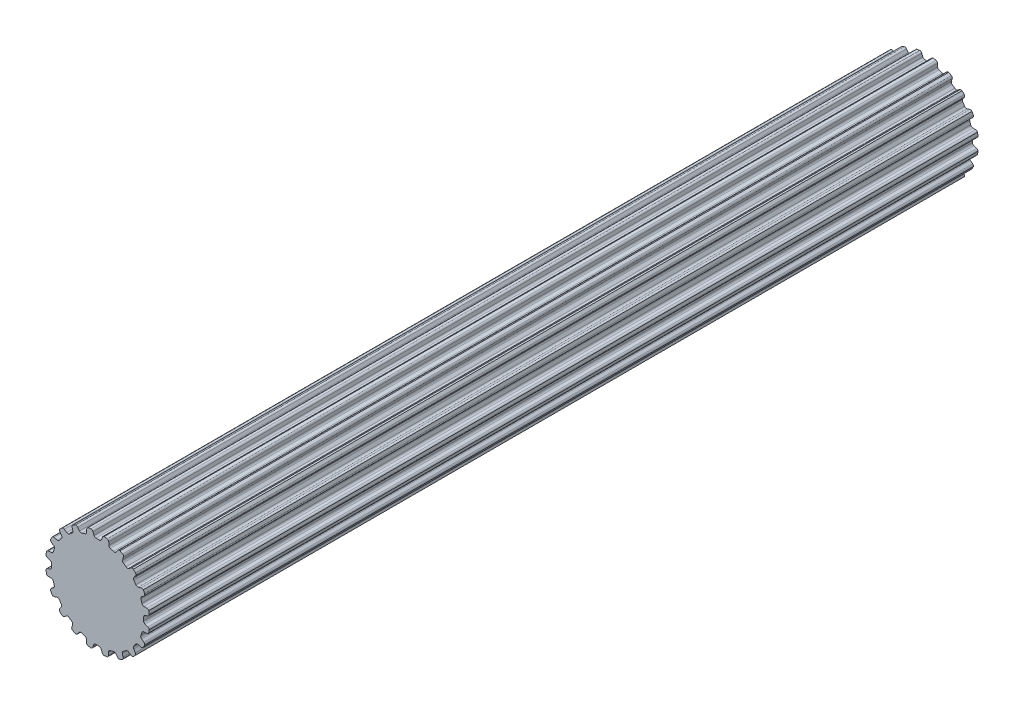
SolidWorks part; units mm, degrees
ref_plane "Front Plane" through (0, 0, 0) normal (0, 0, 1) x (1, 0, 0)
ref_plane "Top Plane" through (0, 0, 0) normal (0, 1, 0) x (1, 0, 0)
ref_plane "Right Plane" through (0, 0, 0) normal (1, 0, 0) x (0, 0, -1)
sketch "Sketch1" plane through (0, 0, 0) normal (0, 0, 1) x (1, 0, 0)
  line L0 (-0.1069, 2.9699) -> (0.1069, 2.9699)
  line L1 (0.3159, 3.2375) -> (0.2537, 3.0575)
  line L2 (-0.2964, 3.2367) -> (-0.2318, 3.0575)
  line L3 (-0.2964, 3.2367) -> (0.3159, 3.2375) construction
  line L4 (0, 3.3252) -> (0, 0) construction
  line L5 (-0.2318, 3.0575) -> (0.2537, 3.0575) construction
  line L6 (-0.4281, 3.3241) -> (0.4281, 3.3263) construction
  line L7 (0.7183, 3.1698) -> (0.7244, 2.9795)
  line L8 (0.816, 2.8576) -> (1.0195, 2.7915)
  line L9 (1.3009, 2.9815) -> (1.1862, 2.8295)
  line L10 (1.6627, 2.7927) -> (1.6097, 2.6099)
  line L11 (1.6591, 2.4655) -> (1.8322, 2.3398)
  line L12 (2.1585, 2.4335) -> (2.0025, 2.3245)
  line L13 (2.4443, 2.1423) -> (2.3374, 1.9847)
  line L14 (2.3398, 1.8322) -> (2.4655, 1.6591)
  line L15 (2.8049, 1.6474) -> (2.6228, 1.5919)
  line L16 (2.9866, 1.2821) -> (2.8363, 1.1653)
  line L17 (2.7915, 1.0195) -> (2.8576, 0.816)
  line L18 (3.1767, 0.7) -> (2.9863, 0.7035)
  line L19 (3.2367, 0.2964) -> (3.0575, 0.2318)
  line L20 (2.9699, 0.1069) -> (2.9699, -0.1069)
  line L21 (3.2375, -0.3159) -> (3.0575, -0.2537)
  line L22 (3.1698, -0.7183) -> (2.9795, -0.7244)
  line L23 (2.8576, -0.816) -> (2.7915, -1.0195)
  line L24 (2.9815, -1.3009) -> (2.8295, -1.1862)
  line L25 (2.7927, -1.6627) -> (2.6099, -1.6097)
  line L26 (2.4655, -1.6591) -> (2.3398, -1.8322)
  line L27 (2.4335, -2.1585) -> (2.3245, -2.0025)
  line L28 (2.1423, -2.4443) -> (1.9847, -2.3374)
  line L29 (1.8322, -2.3398) -> (1.6591, -2.4655)
  line L30 (1.6474, -2.8049) -> (1.5919, -2.6228)
  line L31 (1.2821, -2.9866) -> (1.1653, -2.8363)
  line L32 (1.0195, -2.7915) -> (0.816, -2.8576)
  line L33 (0.7, -3.1767) -> (0.7035, -2.9863)
  line L34 (0.2964, -3.2367) -> (0.2318, -3.0575)
  line L35 (0.1069, -2.9699) -> (-0.1069, -2.9699)
  line L36 (-0.3159, -3.2375) -> (-0.2537, -3.0575)
  line L37 (-0.7183, -3.1698) -> (-0.7244, -2.9795)
  line L38 (-0.816, -2.8576) -> (-1.0195, -2.7915)
  line L39 (-1.3009, -2.9815) -> (-1.1862, -2.8295)
  line L40 (-1.6627, -2.7927) -> (-1.6097, -2.6099)
  line L41 (-1.6591, -2.4655) -> (-1.8322, -2.3398)
  line L42 (-2.1585, -2.4335) -> (-2.0025, -2.3245)
  line L43 (-2.4443, -2.1423) -> (-2.3374, -1.9847)
  line L44 (-2.3398, -1.8322) -> (-2.4655, -1.6591)
  line L45 (-2.8049, -1.6474) -> (-2.6228, -1.5919)
  line L46 (-2.9866, -1.2821) -> (-2.8363, -1.1653)
  line L47 (-2.7915, -1.0195) -> (-2.8576, -0.816)
  line L48 (-3.1767, -0.7) -> (-2.9863, -0.7035)
  line L49 (-3.2367, -0.2964) -> (-3.0575, -0.2318)
  line L50 (-2.9699, -0.1069) -> (-2.9699, 0.1069)
  line L51 (-3.2375, 0.3159) -> (-3.0575, 0.2537)
  line L52 (-3.1698, 0.7183) -> (-2.9795, 0.7244)
  line L53 (-2.8576, 0.816) -> (-2.7915, 1.0195)
  line L54 (-2.9815, 1.3009) -> (-2.8295, 1.1862)
  line L55 (-2.7927, 1.6627) -> (-2.6099, 1.6097)
  line L56 (-2.4655, 1.6591) -> (-2.3398, 1.8322)
  line L57 (-2.4335, 2.1585) -> (-2.3245, 2.0025)
  line L58 (-2.1423, 2.4443) -> (-1.9847, 2.3374)
  line L59 (-1.8322, 2.3398) -> (-1.6591, 2.4655)
  line L60 (-1.6474, 2.8049) -> (-1.5919, 2.6228)
  line L61 (-1.2821, 2.9866) -> (-1.1653, 2.8363)
  line L62 (-1.0195, 2.7915) -> (-0.816, 2.8576)
  line L63 (-0.7, 3.1767) -> (-0.7035, 2.9863)
  line L64 (0.4281, 3.3263) -> (0.62, 3.2938)
  line L65 (1.4351, 3.0312) -> (1.6075, 2.9409)
  line L66 (2.3015, 2.4394) -> (2.4376, 2.3003)
  line L67 (2.9427, 1.6088) -> (3.0291, 1.4344)
  line L68 (3.2958, 0.6207) -> (3.3241, 0.4281)
  line L69 (3.3263, -0.4281) -> (3.2938, -0.62)
  line L70 (3.0312, -1.4351) -> (2.9409, -1.6075)
  line L71 (2.4394, -2.3015) -> (2.3003, -2.4376)
  line L72 (1.6088, -2.9427) -> (1.4344, -3.0291)
  line L73 (0.6207, -3.2958) -> (0.4281, -3.3241)
  line L74 (-0.4281, -3.3263) -> (-0.62, -3.2938)
  line L75 (-1.4351, -3.0312) -> (-1.6075, -2.9409)
  line L76 (-2.3015, -2.4394) -> (-2.4376, -2.3003)
  line L77 (-2.9427, -1.6088) -> (-3.0291, -1.4344)
  line L78 (-3.2958, -0.6207) -> (-3.3241, -0.4281)
  line L79 (-3.3263, 0.4281) -> (-3.2938, 0.62)
  line L80 (-3.0312, 1.4351) -> (-2.9409, 1.6075)
  line L81 (-2.4394, 2.3015) -> (-2.3003, 2.4376)
  line L82 (-1.6088, 2.9427) -> (-1.4344, 3.0291)
  line L83 (-0.6207, 3.2958) -> (-0.4281, 3.3241)
  arc A0 (0.2537, 3.0575) -> (0.1069, 2.9699) centre (0.1283, 3.1009) cw
  arc A1 (-0.2318, 3.0575) -> (-0.1069, 2.9699) centre (-0.1069, 3.1026) ccw
  arc A2 (0.62, 3.2938) -> (0.7183, 3.1698) centre (0.5856, 3.1656) cw
  arc A3 (0.7244, 2.9795) -> (0.816, 2.8576) centre (0.857, 2.9838) ccw
  arc A4 (-0.4281, 3.3241) -> (-0.2964, 3.2367) centre (-0.4213, 3.1916) cw
  arc A5 (0.4281, 3.3263) -> (0.3159, 3.2375) centre (0.4413, 3.1942) ccw
  arc A6 (1.1862, 2.8295) -> (1.0195, 2.7915) centre (1.0802, 2.9095) cw
  arc A7 (1.4351, 3.0312) -> (1.3009, 2.9815) centre (1.4068, 2.9015) ccw
  arc A8 (1.6075, 2.9409) -> (1.6627, 2.7927) centre (1.5352, 2.8297) cw
  arc A9 (1.6097, 2.6099) -> (1.6591, 2.4655) centre (1.7371, 2.5729) ccw
  arc A10 (2.0025, 2.3245) -> (1.8322, 2.3398) centre (1.9264, 2.4332) cw
  arc A11 (2.3015, 2.4394) -> (2.1585, 2.4335) centre (2.2346, 2.3248) ccw
  arc A12 (2.4376, 2.3003) -> (2.4443, 2.1423) centre (2.3345, 2.2168) cw
  arc A13 (2.3374, 1.9847) -> (2.3398, 1.8322) centre (2.4472, 1.9102) ccw
  arc A14 (2.6228, 1.5919) -> (2.4655, 1.6591) centre (2.5841, 1.7189) cw
  arc A15 (2.9427, 1.6088) -> (2.8049, 1.6474) centre (2.8436, 1.5205) ccw
  arc A16 (3.0291, 1.4344) -> (2.9866, 1.2821) centre (2.9052, 1.3869) cw
  arc A17 (2.8363, 1.1653) -> (2.7915, 1.0195) centre (2.9177, 1.0605) ccw
  arc A18 (2.9863, 0.7035) -> (2.8576, 0.816) centre (2.9887, 0.8362) cw
  arc A19 (3.2958, 0.6207) -> (3.1767, 0.7) centre (3.1743, 0.5673) ccw
  arc A20 (3.3241, 0.4281) -> (3.2367, 0.2964) centre (3.1916, 0.4213) cw
  arc A21 (3.0575, 0.2318) -> (2.9699, 0.1069) centre (3.1026, 0.1069) ccw
  arc A22 (3.0575, -0.2537) -> (2.9699, -0.1069) centre (3.1009, -0.1283) cw
  arc A23 (3.3263, -0.4281) -> (3.2375, -0.3159) centre (3.1942, -0.4413) ccw
  arc A24 (3.2938, -0.62) -> (3.1698, -0.7183) centre (3.1656, -0.5856) cw
  arc A25 (2.9795, -0.7244) -> (2.8576, -0.816) centre (2.9838, -0.857) ccw
  arc A26 (2.8295, -1.1862) -> (2.7915, -1.0195) centre (2.9095, -1.0802) cw
  arc A27 (3.0312, -1.4351) -> (2.9815, -1.3009) centre (2.9015, -1.4068) ccw
  arc A28 (2.9409, -1.6075) -> (2.7927, -1.6627) centre (2.8297, -1.5352) cw
  arc A29 (2.6099, -1.6097) -> (2.4655, -1.6591) centre (2.5729, -1.7371) ccw
  arc A30 (2.3245, -2.0025) -> (2.3398, -1.8322) centre (2.4332, -1.9264) cw
  arc A31 (2.4394, -2.3015) -> (2.4335, -2.1585) centre (2.3248, -2.2346) ccw
  arc A32 (2.3003, -2.4376) -> (2.1423, -2.4443) centre (2.2168, -2.3345) cw
  arc A33 (1.9847, -2.3374) -> (1.8322, -2.3398) centre (1.9102, -2.4472) ccw
  arc A34 (1.5919, -2.6228) -> (1.6591, -2.4655) centre (1.7189, -2.5841) cw
  arc A35 (1.6088, -2.9427) -> (1.6474, -2.8049) centre (1.5205, -2.8436) ccw
  arc A36 (1.4344, -3.0291) -> (1.2821, -2.9866) centre (1.3869, -2.9052) cw
  arc A37 (1.1653, -2.8363) -> (1.0195, -2.7915) centre (1.0605, -2.9177) ccw
  arc A38 (0.7035, -2.9863) -> (0.816, -2.8576) centre (0.8362, -2.9887) cw
  arc A39 (0.6207, -3.2958) -> (0.7, -3.1767) centre (0.5673, -3.1743) ccw
  arc A40 (0.4281, -3.3241) -> (0.2964, -3.2367) centre (0.4213, -3.1916) cw
  arc A41 (0.2318, -3.0575) -> (0.1069, -2.9699) centre (0.1069, -3.1026) ccw
  arc A42 (-0.2537, -3.0575) -> (-0.1069, -2.9699) centre (-0.1283, -3.1009) cw
  arc A43 (-0.4281, -3.3263) -> (-0.3159, -3.2375) centre (-0.4413, -3.1942) ccw
  arc A44 (-0.62, -3.2938) -> (-0.7183, -3.1698) centre (-0.5856, -3.1656) cw
  arc A45 (-0.7244, -2.9795) -> (-0.816, -2.8576) centre (-0.857, -2.9838) ccw
  arc A46 (-1.1862, -2.8295) -> (-1.0195, -2.7915) centre (-1.0802, -2.9095) cw
  arc A47 (-1.4351, -3.0312) -> (-1.3009, -2.9815) centre (-1.4068, -2.9015) ccw
  arc A48 (-1.6075, -2.9409) -> (-1.6627, -2.7927) centre (-1.5352, -2.8297) cw
  arc A49 (-1.6097, -2.6099) -> (-1.6591, -2.4655) centre (-1.7371, -2.5729) ccw
  arc A50 (-2.0025, -2.3245) -> (-1.8322, -2.3398) centre (-1.9264, -2.4332) cw
  arc A51 (-2.3015, -2.4394) -> (-2.1585, -2.4335) centre (-2.2346, -2.3248) ccw
  arc A52 (-2.4376, -2.3003) -> (-2.4443, -2.1423) centre (-2.3345, -2.2168) cw
  arc A53 (-2.3374, -1.9847) -> (-2.3398, -1.8322) centre (-2.4472, -1.9102) ccw
  arc A54 (-2.6228, -1.5919) -> (-2.4655, -1.6591) centre (-2.5841, -1.7189) cw
  arc A55 (-2.9427, -1.6088) -> (-2.8049, -1.6474) centre (-2.8436, -1.5205) ccw
  arc A56 (-3.0291, -1.4344) -> (-2.9866, -1.2821) centre (-2.9052, -1.3869) cw
  arc A57 (-2.8363, -1.1653) -> (-2.7915, -1.0195) centre (-2.9177, -1.0605) ccw
  arc A58 (-2.9863, -0.7035) -> (-2.8576, -0.816) centre (-2.9887, -0.8362) cw
  arc A59 (-3.2958, -0.6207) -> (-3.1767, -0.7) centre (-3.1743, -0.5673) ccw
  arc A60 (-3.3241, -0.4281) -> (-3.2367, -0.2964) centre (-3.1916, -0.4213) cw
  arc A61 (-3.0575, -0.2318) -> (-2.9699, -0.1069) centre (-3.1026, -0.1069) ccw
  arc A62 (-3.0575, 0.2537) -> (-2.9699, 0.1069) centre (-3.1009, 0.1283) cw
  arc A63 (-3.3263, 0.4281) -> (-3.2375, 0.3159) centre (-3.1942, 0.4413) ccw
  arc A64 (-3.2938, 0.62) -> (-3.1698, 0.7183) centre (-3.1656, 0.5856) cw
  arc A65 (-2.9795, 0.7244) -> (-2.8576, 0.816) centre (-2.9838, 0.857) ccw
  arc A66 (-2.8295, 1.1862) -> (-2.7915, 1.0195) centre (-2.9095, 1.0802) cw
  arc A67 (-3.0312, 1.4351) -> (-2.9815, 1.3009) centre (-2.9015, 1.4068) ccw
  arc A68 (-2.9409, 1.6075) -> (-2.7927, 1.6627) centre (-2.8297, 1.5352) cw
  arc A69 (-2.6099, 1.6097) -> (-2.4655, 1.6591) centre (-2.5729, 1.7371) ccw
  arc A70 (-2.3245, 2.0025) -> (-2.3398, 1.8322) centre (-2.4332, 1.9264) cw
  arc A71 (-2.4394, 2.3015) -> (-2.4335, 2.1585) centre (-2.3248, 2.2346) ccw
  arc A72 (-2.3003, 2.4376) -> (-2.1423, 2.4443) centre (-2.2168, 2.3345) cw
  arc A73 (-1.9847, 2.3374) -> (-1.8322, 2.3398) centre (-1.9102, 2.4472) ccw
  arc A74 (-1.5919, 2.6228) -> (-1.6591, 2.4655) centre (-1.7189, 2.5841) cw
  arc A75 (-1.6088, 2.9427) -> (-1.6474, 2.8049) centre (-1.5205, 2.8436) ccw
  arc A76 (-1.4344, 3.0291) -> (-1.2821, 2.9866) centre (-1.3869, 2.9052) cw
  arc A77 (-1.1653, 2.8363) -> (-1.0195, 2.7915) centre (-1.0605, 2.9177) ccw
  arc A78 (-0.7035, 2.9863) -> (-0.816, 2.8576) centre (-0.8362, 2.9887) cw
  arc A79 (-0.6207, 3.2958) -> (-0.7, 3.1767) centre (-0.5673, 3.1743) ccw
  point P14 (0, 2.9699)
  point P247 (0, 0)
  dimension "D4" = 0.1327
  dimension "D8" = 20
  dimension "D1" = 2.9699
  dimension "D2" = 0.2139
  dimension "D3" = 0.1904
  dimension "D5" = 0.0877
  dimension "D6" = 0.4855
  dimension "D7" = 0.8563
extrude "Boss-Extrude1" add sketch "Sketch1" along normal mid plane 53.4111
sketch "Sketch2" plane through (0, 0, 26.7056) normal (0, 0, 1) x (1, 0, 0)
  circle A0 centre (0, 0) radius 3.3516 construction
sketch "Sketch3" plane through (0, 0, -26.7056) normal (0, 0, -1) x (-1, 0, 0)
  circle A0 centre (0, 0) radius 3.3516 construction
  circle A1 centre (0, 0) radius 3.3516 construction
